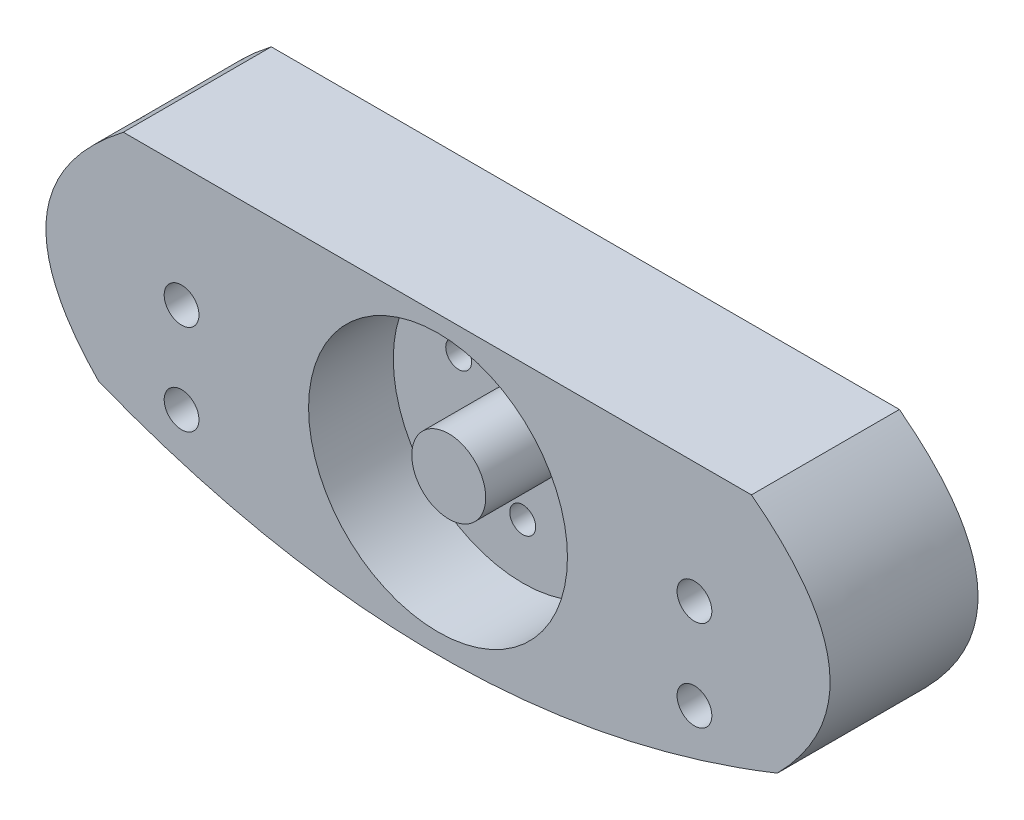
SolidWorks part; units mm, degrees
ref_plane "Front Plane" through (0, 0, 0) normal (0, 0, 1) x (1, 0, 0)
ref_plane "Top Plane" through (0, 0, 0) normal (0, 1, 0) x (1, 0, 0)
ref_plane "Right Plane" through (0, 0, 0) normal (1, 0, 0) x (0, 0, -1)
sketch "Sketch2" plane through (0, 0, 0) normal (0, 0, 1) x (1, 0, 0)
  line L1 (42.3768, 8.6832) -> (-42.5401, 8.6832)
  line L2 (42.3768, 8.6832) -> (-42.5401, 8.6832)
  parabola Q3 (45.8737, -22.1555) -> (42.3768, 8.6832) focus (46.195, -7.6248) apex (52.9944, -7.3425)
  parabola Q4 (-42.5401, 8.6832) -> (-45.8737, -22.1555) focus (-46.1445, -7.62) apex (-52.997, -7.3593)
  parabola Q5 (-45.8737, -22.1555) -> (45.8737, -22.1555) focus (0.744, 26.3908) apex (1.3864, -31.2701)
  parabola Q6 (45.8737, -22.1555) -> (42.3768, 8.6832) focus (46.195, -7.6248) apex (52.9944, -7.3425)
  parabola Q7 (-42.5401, 8.6832) -> (-45.8737, -22.1555) focus (-46.1445, -7.62) apex (-52.997, -7.3593)
  parabola Q8 (-45.8737, -22.1555) -> (45.8737, -22.1555) focus (0.744, 26.3908) apex (1.3864, -31.2701)
  dimension "D1" = 0
extrude "Boss-Extrude1" add sketch "Sketch2" along normal blind 20
sketch "Sketch4" plane through (0, 0, 20) normal (0, 0, 1) x (1, 0, 0)
  line L1 (0, -17) -> (0, -2) construction
  circle A1 centre (0, -11.063) radius 17.5
  dimension "D1" = 35
extrude "Cut-Extrude1" cut sketch "Sketch4" against normal blind 11.4533
sketch "Sketch5" plane through (0, 0, 8.5467) normal (0, 0, 1) x (1, 0, 0)
  line L0 (0, -17) -> (0, -2) construction
  circle A1 centre (0, -11.063) radius 5
  circle A2 centre (0, -11.063) radius 17.5 construction
  dimension "D1" = 10
extrude "Boss-Extrude2" add sketch "Sketch5" along normal blind 10
sketch "Sketch6" plane through (0, 0, 8.5467) normal (0, 0, 1) x (1, 0, 0)
  line L0 (0, -17) -> (0, -2) construction
  line L1 (0, -21.1295) -> (8.6603, -6.1295)
  line L2 (8.6603, -6.1295) -> (-8.6603, -6.1295)
  line L3 (-8.6603, -6.1295) -> (0, -21.1295)
  circle A0 centre (0, -11.1295) radius 10
  dimension "D1" = 20
hole_wizard "CBORE for M5 Hex Head Machine Screw2" positions "Sketch9" profile "Sketch10" counterbore size "M5" standard "ANSI Metric"
sketch "Sketch9" plane through (0, 0, 0) normal (0, 0, -1) x (-1, 0, 0)
  point P0 (-8.6603, -6.1295)
  point P3 (0, -21.1295)
  point P6 (8.6603, -6.1295)
sketch "Sketch10" plane through (8.6603, -6.1295, 0) normal (1, 0, 0) x (0, 1, 0)
  line L0 (0, 0) -> (0, 12.75)
  line L1 (0, 12.75) -> (1.75, 11)
  line L2 (1.75, 11) -> (1.75, 4)
  line L3 (1.75, 4) -> (3.5, 4)
  line L4 (3.5, 4) -> (3.5, 0)
  line L5 (3.5, 0) -> (0, 0)
  line L10 (0, 12.75) -> (-1.75, 11) construction
  line L11 (0, -6.35) -> (0, 107.95) construction
  dimension "Hole Dia." = 3.5
  dimension "Hole Depth" = 11
  dimension "C'Bore Dia." = 7
  dimension "C'Bore Depth" = 4
  dimension "Drill Angle" = 90
sketch "Sketch11" plane through (0, 0, 20) normal (0, 0, 1) x (1, 0, 0)
  circle A0 centre (-34.6698, -19.8652) radius 2.35 construction
  circle A1 centre (-34.6698, -7.6169) radius 2.35 construction
  circle A2 centre (34.6698, -7.6169) radius 2.35 construction
  circle A3 centre (34.6698, -19.8652) radius 2.35 construction
  circle A4 centre (-34.6698, -19.8652) radius 2.35
  circle A5 centre (-34.6698, -7.6169) radius 2.35
  circle A6 centre (34.6698, -7.6169) radius 2.35
  circle A7 centre (34.6698, -19.8652) radius 2.35
extrude "Cut-Extrude2" cut sketch "Sketch11" against normal through all both and the other way through all
